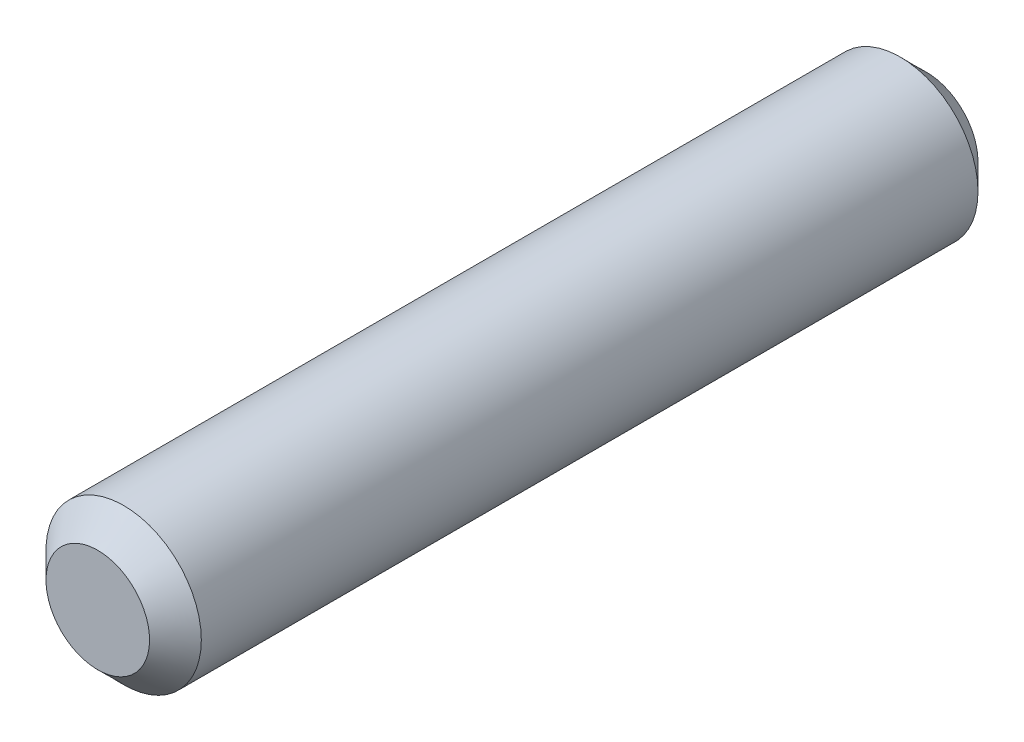
SolidWorks part; units mm, degrees
material "AISI 316 Barre d'acier inoxydable recuit (SS)"
ref_plane "Plan de face" through (0, 0, 0) normal (0, 0, 1) x (1, 0, 0)
ref_plane "Plan de dessus" through (0, 0, 0) normal (0, 1, 0) x (1, 0, 0)
ref_plane "Plan de droite" through (0, 0, 0) normal (1, 0, 0) x (0, 0, -1)
sketch "Esquisse1" plane through (0, 0, 0) normal (0, 0, 1) x (1, 0, 0)
  circle A0 centre (0, 0) radius 1.5
  dimension "D1" = 3
extrude "Boss.-Extru.1" add sketch "Esquisse1" along normal mid plane 16
chamfer "Chanfrein1" distance 0.5 angle 45 2 edges at (1.5, 0, -8) (1.5, 0, 8)
